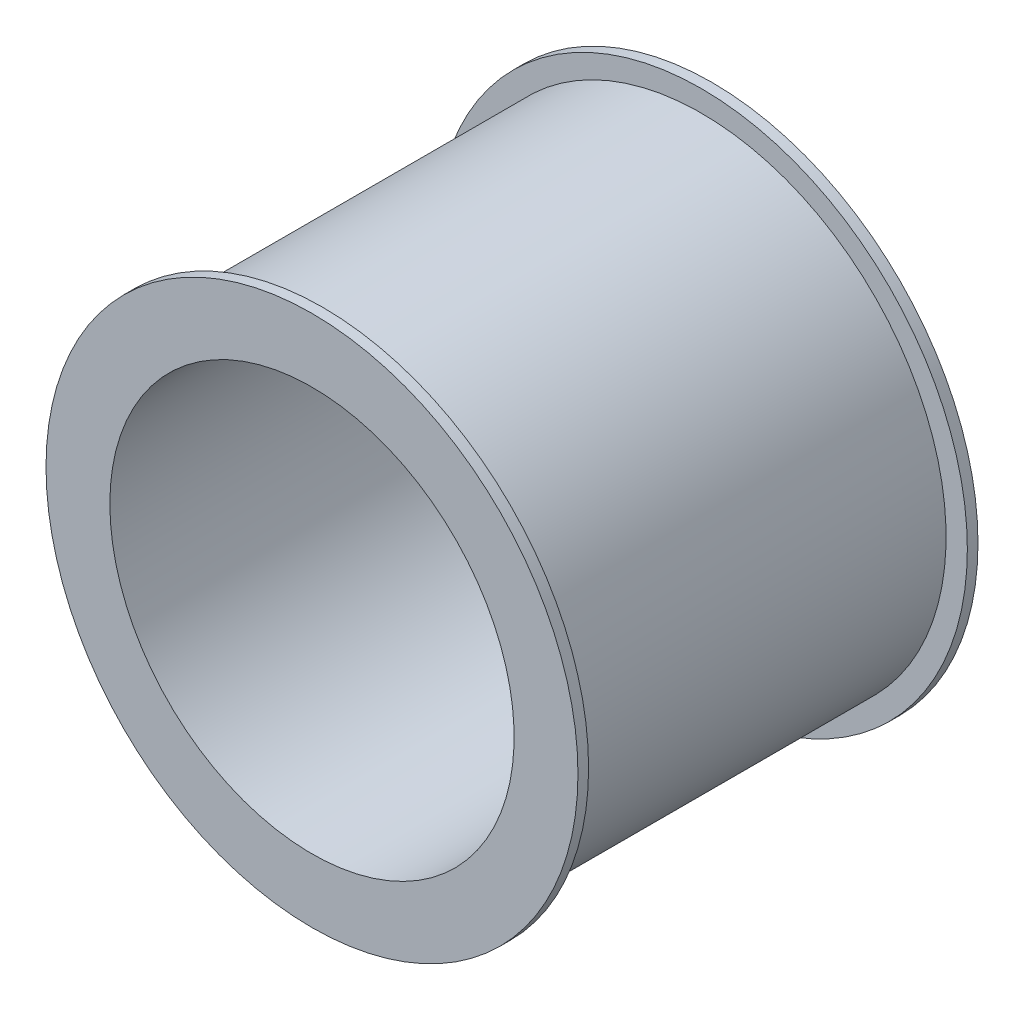
SolidWorks part; units mm, degrees
material "201 Annealed Stainless Steel (SS)"
ref_plane "Front Plane" through (0, 0, 0) normal (0, 0, 1) x (1, 0, 0)
ref_plane "Top Plane" through (0, 0, 0) normal (0, 1, 0) x (1, 0, 0)
ref_plane "Right Plane" through (0, 0, 0) normal (1, 0, 0) x (0, 0, -1)
sketch "Sketch1" plane through (0, 0, 0) normal (0, 0, 1) x (1, 0, 0)
  circle A0 centre (0, 0) radius 11.5
  circle A1 centre (0, 0) radius 9.5
  dimension "D1" = 23
  dimension "D2" = 2
extrude "Boss-Extrude1" add sketch "Sketch1" along normal blind 18.8 contours A0 | A1
sketch "Sketch2" plane through (0, 0, 18.8) normal (0, 0, 1) x (1, 0, 0)
  circle A0 centre (0, 0) radius 11.5 construction
  circle A1 centre (0, 0) radius 11.5
  circle A2 centre (0, 0) radius 12.5
  dimension "D1" = 1
extrude "Boss-Extrude3" add sketch "Sketch2" against normal blind 0.5
sketch "Sketch3" plane through (0, 0, 0) normal (0, 0, -1) x (-1, 0, 0)
  circle A0 centre (0, 0) radius 11.5 construction
  circle A1 centre (0, 0) radius 11.5
  circle A2 centre (0, 0) radius 12.5
  circle M3 centre (0, 0) radius 11.5
  circle M4 centre (0, 0) radius 9.5
  dimension "D1" = 1
extrude "Boss-Extrude4" add sketch "Sketch3" against normal blind 0.5 contours A2 M3 | M4
